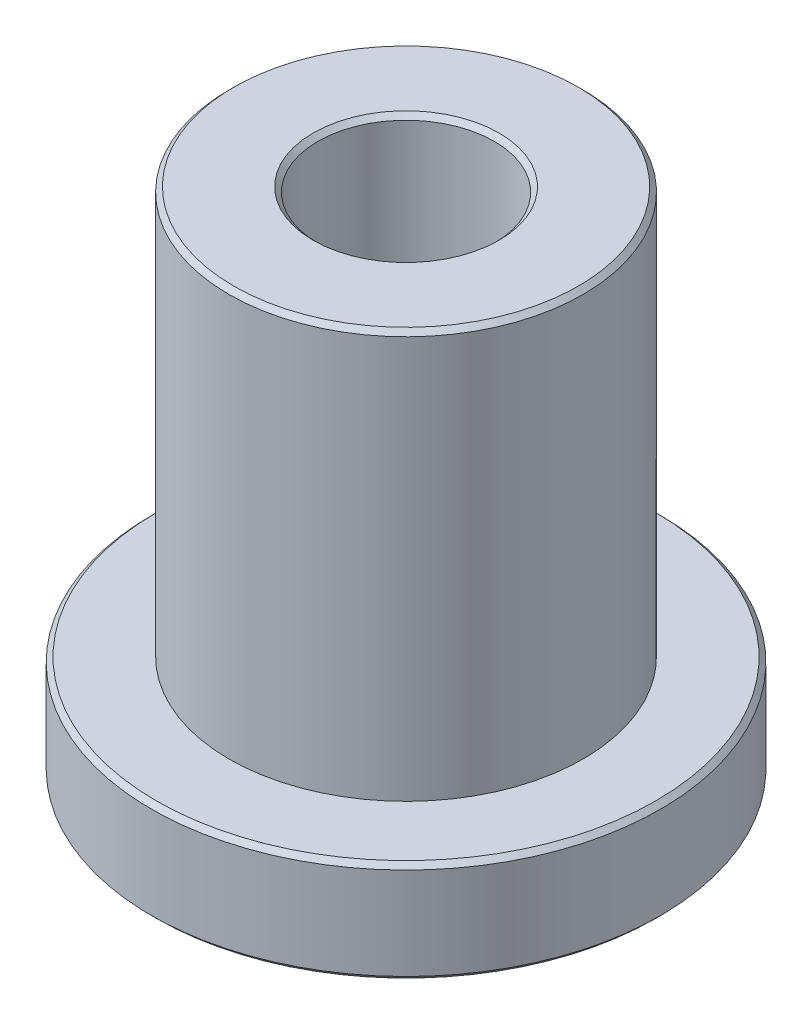
SolidWorks part; units mm, degrees
material "Nylon 101"
ref_plane "Front Plane" through (0, 0, 0) normal (0, 0, 1) x (1, 0, 0)
ref_plane "Top Plane" through (0, 0, 0) normal (0, 1, 0) x (1, 0, 0)
ref_plane "Right Plane" through (0, 0, 0) normal (1, 0, 0) x (0, 0, -1)
sketch "Sketch1" plane through (0, 0, 0) normal (0, 1, 0) x (1, 0, 0)
  circle A0 centre (0, 0) radius 11.049
  dimension "D1" = 22.098
extrude "Boss-Extrude1" add sketch "Sketch1" along normal blind 25.4
sketch "Sketch2" plane through (0, 0, 0) normal (0, -1, 0) x (1, 0, 0)
  circle A0 centre (0, 0) radius 15.875
  dimension "D1" = 31.75
extrude "Boss-Extrude2" add sketch "Sketch2" along normal blind 6.35
sketch "Sketch3" plane through (0, -6.35, 0) normal (0, -1, 0) x (1, 0, 0)
  circle A0 centre (0, 0) radius 5.5
  dimension "D1" = 11
extrude "Cut-Extrude1" cut sketch "Sketch3" against normal through all
sketch "Sketch4" plane through (0, -6.35, 0) normal (0, -1, 0) x (1, 0, 0)
  circle A0 centre (0, 0) radius 11.1125
  dimension "D1" = 22.225
ref_plane "Plane1" through (0, 9.525, 0) normal (0, 1, 0) x (1, 0, 0)
chamfer "Chamfer1" distance 0.3 angle 45 5 edges at (0, 0, -15.875) (0, -6.35, -15.875) (0, 25.4, 11.049) (0, 25.4, -5.5) (0, -6.35, -5.5)
equation "\"D1@Chamfer1\"=.3mm"
